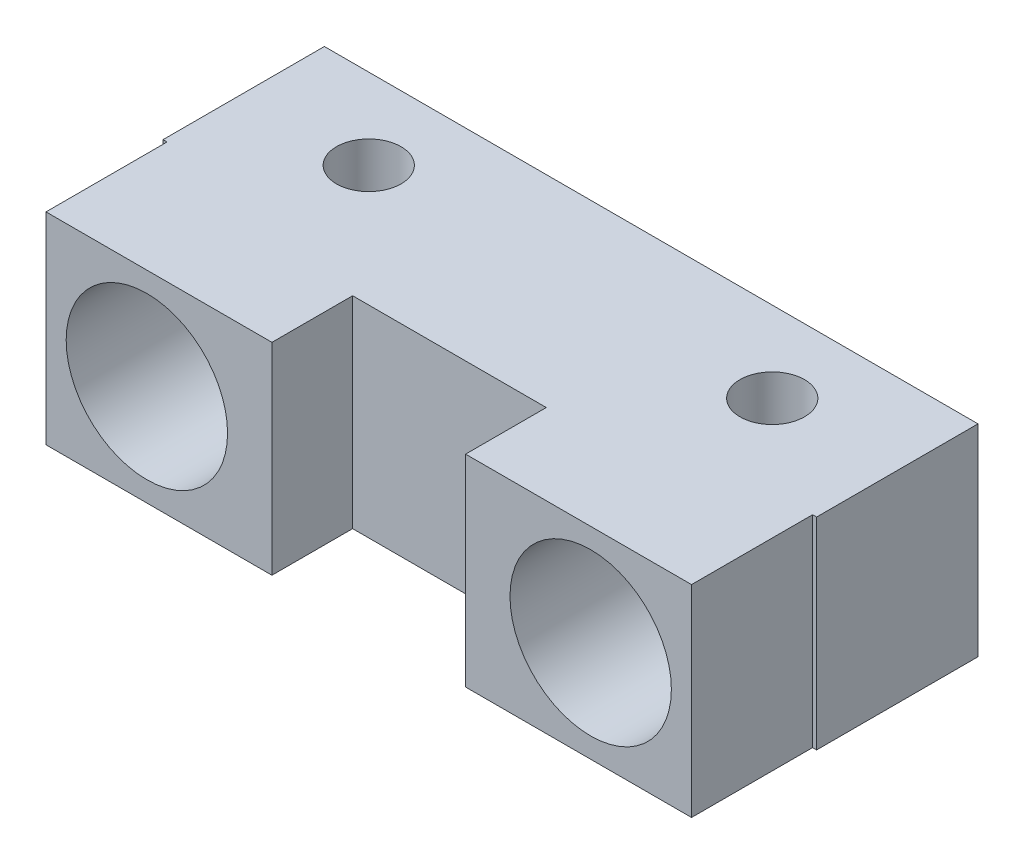
SolidWorks part; units mm, degrees
ref_plane "Front Plane" through (0, 0, 0) normal (0, 0, 1) x (1, 0, 0)
ref_plane "Top Plane" through (0, 0, 0) normal (0, 1, 0) x (1, 0, 0)
ref_plane "Right Plane" through (0, 0, 0) normal (1, 0, 0) x (0, 0, -1)
sketch "Sketch1" plane through (0, 0, 0) normal (0, 1, 0) x (1, 0, 0)
  line L0 (0, 10) -> (0, -10) construction
  line L1 (-40.5, -10) -> (-40, -10)
  line L2 (-40.5, -10) -> (-40.5, 10)
  line L3 (-40.5, 10) -> (40.5, 10)
  line L4 (40.5, -10) -> (40.5, 10)
  line L5 (-40.5, -10) -> (40.5, 10) construction
  line L6 (-40.5, 10) -> (40.5, -10) construction
  line L7 (-40.5, 0) -> (40.5, 0) construction
  line L8 (-40, -10) -> (-40, -25)
  line L9 (-40, -25) -> (40, -25)
  line L10 (40, -10) -> (40, -25)
  line L11 (40, -10) -> (40.5, -10)
  circle A0 centre (-25, 0) radius 4
  circle A1 centre (25, 0) radius 4
  point P0 (0, 0)
  dimension "D3" = 8
  dimension "D4" = 50
  dimension "D1" = 20
  dimension "D2" = 81
  dimension "D5" = 80
  dimension "D6" = 15
extrude "Boss-Extrude1" add sketch "Sketch1" along normal mid plane 25
sketch "Sketch2" plane through (0, 0, 25) normal (0, 0, 1) x (1, 0, 0)
  line L0 (-40, 0) -> (40, 0) construction
  line L1 (-40, 12.5) -> (-40, -12.5) construction
  line L2 (40, 12.5) -> (40, -12.5) construction
  line L3 (0, 12.5) -> (0, -12.5) construction
  line L4 (-40, 12.5) -> (40, 12.5) construction
  line L5 (-40, -12.5) -> (40, -12.5) construction
  circle A0 centre (-27.5, 0) radius 10
  circle A1 centre (27.5, 0) radius 10
  dimension "D1" = 20
  dimension "D2" = 55
extrude "Cut-Extrude1" cut sketch "Sketch2" against normal blind 15
sketch "Sketch3" plane through (0, 0, 25) normal (0, 0, 1) x (1, 0, 0)
  line L0 (0, 12.5) -> (0, -12.5) construction
  line L1 (-40, 12.5) -> (40, 12.5) construction
  line L2 (-40, -12.5) -> (40, -12.5) construction
  line L4 (-12, -15.5) -> (12, -15.5)
  line L5 (-12, -15.5) -> (-12, 15.5)
  line L6 (-12, 15.5) -> (12, 15.5)
  line L7 (12, -15.5) -> (12, 15.5)
  line L8 (-12, -15.5) -> (12, 15.5) construction
  line L9 (-12, 15.5) -> (12, -15.5) construction
  point P6 (0, 0)
  dimension "D1" = 24
  dimension "D2" = 31
extrude "Cut-Extrude2" cut sketch "Sketch3" against normal blind 10
